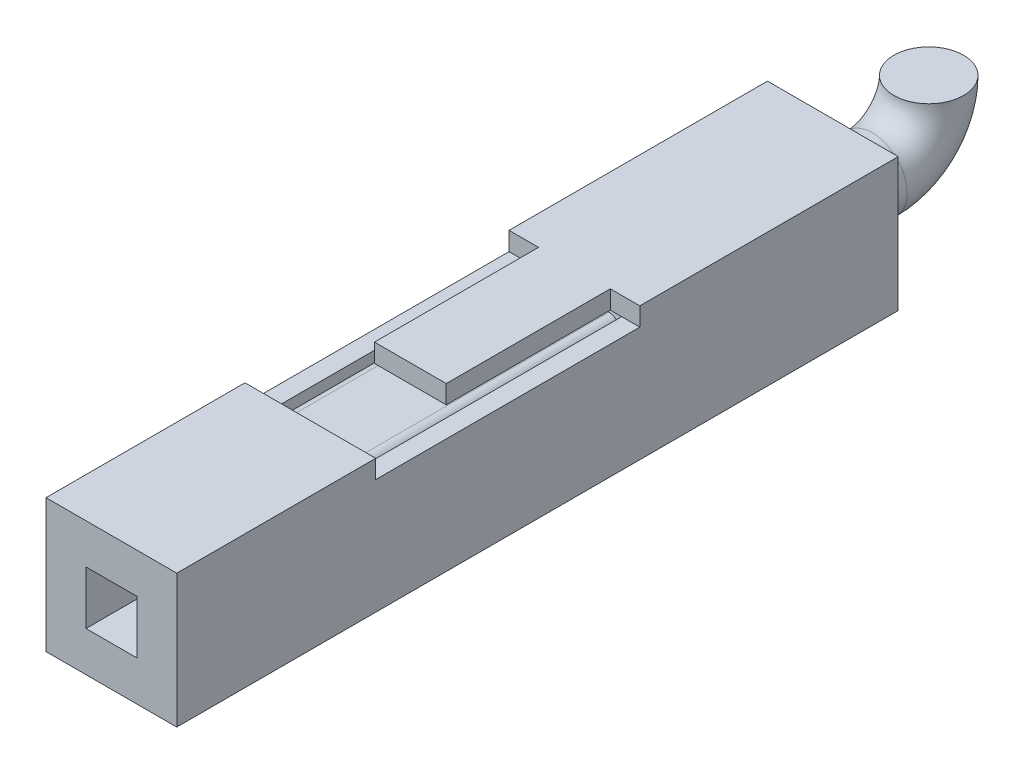
SolidWorks part; units mm, degrees
other "Wire"
ref_plane "Front Plane" through (0, 0, 0) normal (0, 0, 1) x (1, 0, 0)
ref_plane "Top Plane" through (0, 0, 0) normal (0, 1, 0) x (1, 0, 0)
ref_plane "Right Plane" through (0, 0, 0) normal (1, 0, 0) x (0, 0, -1)
sketch "Sketch1" plane through (0, 0, 0) normal (0, 0, 1) x (1, 0, 0)
  line L0 (-0.495, 0.52) -> (0.495, 0.52)
  line L1 (-1.275, 1.3) -> (1.275, 1.3)
  line L2 (-1.275, 1.3) -> (-1.275, -1.3)
  line L3 (-1.275, -1.3) -> (1.275, -1.3)
  line L4 (1.275, 1.3) -> (1.275, -1.3)
  line L5 (-1.275, 1.3) -> (1.275, -1.3) construction
  line L6 (-1.275, -1.3) -> (1.275, 1.3) construction
  line L7 (0.495, 0.52) -> (0.495, -0.52)
  line L8 (-0.495, -0.52) -> (0.495, -0.52)
  line L9 (-0.495, 0.52) -> (-0.495, -0.52)
  point P4 (0, 0)
  dimension "D1" = 2.6
  dimension "D2" = 2.55
  dimension "D3" = 0.78
extrude "Boss-Extrude1" add sketch "Sketch1" along normal blind 14.07
sketch "Sketch2" plane through (-1.275, 0, 0) normal (-1, 0, 0) x (0, 0, 1)
  line L0 (14.07, 1.3) -> (0, 1.3) construction
  line L1 (5.04, 1.3) -> (10.19, 1.3)
  line L2 (5.04, 1.3) -> (5.04, 0.94)
  line L3 (5.04, 0.94) -> (10.19, 0.94)
  line L4 (10.19, 1.3) -> (10.19, 0.94)
  line L5 (5.04, 1.3) -> (10.19, 0.94) construction
  line L6 (5.04, 0.94) -> (10.19, 1.3) construction
  line L7 (14.07, -1.3) -> (0, -1.3) construction
  line L8 (14.07, 1.3) -> (14.07, -1.3) construction
  point P4 (7.615, 1.12)
  dimension "D1" = 2.24
  dimension "D2" = 5.15
  dimension "D3" = 3.88
extrude "Cut-Extrude1" cut sketch "Sketch2" against normal up to next
sketch "Sketch3" plane through (0, 0, 0) normal (0, 0, -1) x (-1, 0, 0)
  line L9 (-1.275, 0.94) -> (1.275, 0.94) construction
  line L10 (-0.9219, 0.94) -> (0.9219, 0.94)
  line L11 (-0.9219, 0.94) -> (-0.9219, -0.94)
  line L12 (-0.9219, -0.94) -> (0.9219, -0.94)
  line L13 (0.9219, 0.94) -> (0.9219, -0.94)
  line L14 (-0.9219, 0.94) -> (0.9219, -0.94) construction
  line L19 (-0.9219, -0.94) -> (0.9219, 0.94) construction
  point P7 (0, 0)
extrude "Cut-Extrude2" cut sketch "Sketch3" against normal blind 12
sketch "Sketch4" plane through (0, 1.3, 0) normal (0, 1, 0) x (1, 0, 0)
  line L0 (1.275, -5.04) -> (-1.275, -5.04) construction
  line L1 (0.7, -5.04) -> (-0.7, -5.04)
  line L2 (0.7, -5.04) -> (0.7, -8.24)
  line L3 (0.7, -8.24) -> (-0.7, -8.24)
  line L4 (-0.7, -5.04) -> (-0.7, -8.24)
  line L5 (0.7, -5.04) -> (-0.7, -8.24) construction
  line L6 (0.7, -8.24) -> (-0.7, -5.04) construction
  line L7 (1.275, 0) -> (-1.275, 0) construction
  point P4 (0, -6.64)
  point P8 (0, -5.04)
  point P13 (0, -5.04)
  dimension "D1" = 1.4
  dimension "D2" = 8.24
extrude "Boss-Extrude2" add sketch "Sketch4" against normal up to surface (0.36 mm away) up to face at (1.0985, 0.94, 7.615)
sketch "Sketch5" plane through (0, 0, 12) normal (0, 0, -1) x (-1, 0, 0)
  line L0 (-0.7753, 0.7925) -> (0.7753, 0.7925)
  line L1 (-0.8753, 0.8925) -> (0.8753, 0.8925)
  line L2 (-0.8753, 0.8925) -> (-0.8753, -0.8925)
  line L3 (-0.8753, -0.8925) -> (0.8753, -0.8925)
  line L4 (0.8753, 0.8925) -> (0.8753, -0.8925)
  line L5 (-0.8753, 0.8925) -> (0.8753, -0.8925) construction
  line L6 (-0.8753, -0.8925) -> (0.8753, 0.8925) construction
  line L7 (0.7753, 0.7925) -> (0.7753, -0.7925)
  line L8 (-0.7753, -0.7925) -> (0.7753, -0.7925)
  line L9 (-0.7753, 0.7925) -> (-0.7753, -0.7925)
  point P4 (0, 0)
  dimension "D1" = 0.1
extrude "Boss-Extrude3" add sketch "Sketch5" along normal up to surface (6.96 mm away) separate body up to face at (-0.9744, 1.084, 5.04)
fillet "Fillet1" radius 0.2 4 edges at (0.7753, 0.7925, 8.52) (-0.7753, 0.7925, 8.52) (-0.7753, -0.7925, 8.52) (0.7753, -0.7925, 8.52)
fillet "Fillet2" radius 0.2 4 edges at (0.8753, -0.8925, 8.52) (0.8753, 0.8925, 8.52) (-0.8753, -0.8925, 8.52) (-0.8753, 0.8925, 8.52)
sketch "Sketch6" plane through (0, 0, 0) normal (1, 0, 0) x (0, 0, -1)
  line L0 (1.87, 3.1002) -> (1.87, 1.1002) construction
  line L1 (-5.04, 0) -> (0.7698, 0)
  line L2 (-5.04, 0.5925) -> (-5.04, -0.5925) construction
  line L3 (1.19, 3.1002) -> (1.19, 1.1002) construction
  line L4 (-5.04, 0.68) -> (0.7698, 0.68) construction
  line L5 (-5.04, -0.68) -> (0.7698, -0.68) construction
  line L6 (2.55, 3.1002) -> (2.55, 1.1002) construction
  line L7 (0, -1.3) -> (0, 1.3) construction
  arc A0 (0.7698, 0) -> (1.87, 1.1002) centre (0.7698, 1.1002) ccw
  arc A1 (0.7698, 0.68) -> (1.19, 1.1002) centre (0.7698, 1.1002) ccw construction
  arc A2 (0.7698, -0.68) -> (2.55, 1.1002) centre (0.7698, 1.1002) ccw construction
  dimension "D1" = 0.68
  dimension "D4" = 0.4202
  dimension "D3" = 2.55
  dimension "D5" = 2
  dimension "D2" = 0.68
ref_plane "Plane1" through (0, 0, 5.04) normal (0, 0, -1) x (-1, 0, 0)
sketch "Sketch7" plane through (0, 0, 5.04) normal (0, 0, -1) x (-1, 0, 0)
  circle A0 centre (0, 0) radius 0.68
  dimension "D1" = 1.36
sweep "Sweep2" add profiles "Sketch7" path "Sketch6"
sketch "Sketch8" plane through (0, 0, 0) normal (1, 0, 0) x (0, 0, -1)
  line L0 (2.55, 1.1002) -> (1.19, 1.1002) construction
  point P0 (1.87, 1.1002)
  point P5 (1.87, 2.6436)
